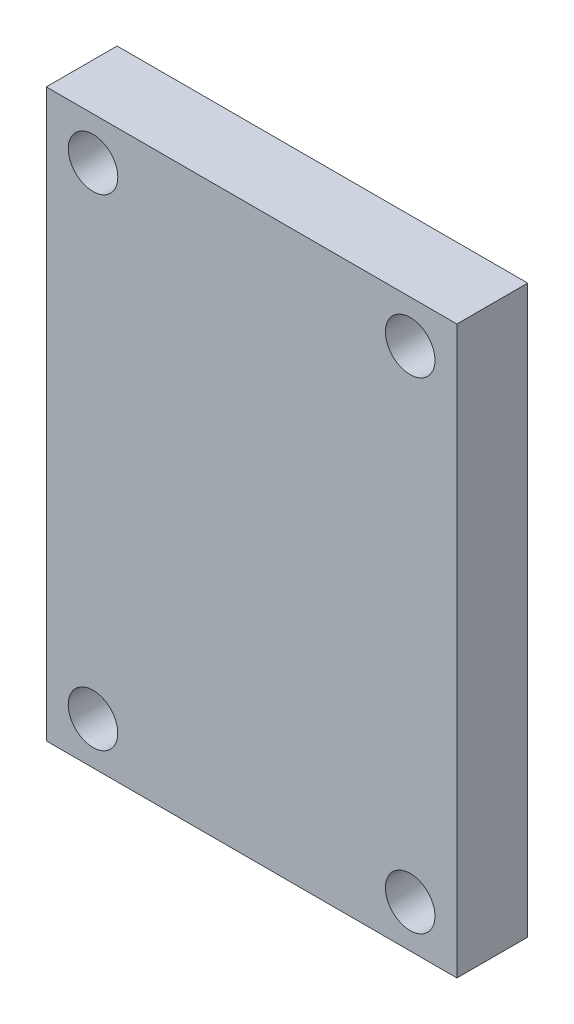
SolidWorks part; units mm, degrees
ref_plane "정면" through (0, 0, 0) normal (0, 0, 1) x (1, 0, 0)
ref_plane "윗면" through (0, 0, 0) normal (0, 1, 0) x (1, 0, 0)
ref_plane "우측면" through (0, 0, 0) normal (1, 0, 0) x (0, 0, -1)
sketch "스케치1" plane through (0, 0, 0) normal (0, 0, 1) x (1, 0, 0)
  line L2 (14.5, -20) -> (-14.5, -20)
  line L3 (14.5, -20) -> (14.5, 20)
  line L4 (14.5, 20) -> (-14.5, 20)
  line L5 (-14.5, -20) -> (-14.5, 20)
  line L6 (14.5, -20) -> (-14.5, 20) construction
  line L7 (14.5, 20) -> (-14.5, -20) construction
  line L9 (-14.5, 17) -> (14.5, 17) construction
  line L10 (-14.5, 0) -> (14.5, 0) construction
  circle A0 centre (11.1994, 17) radius 1.75
  circle A1 centre (-11.1994, 17) radius 1.75
  circle A2 centre (11.1994, -17) radius 1.75
  circle A6 centre (-11.1994, -17) radius 1.75
  point P3 (0, 0)
  dimension "D3" = 40
  dimension "D1" = 3
extrude "보스-돌출1" add sketch "스케치1" along normal blind 5
ref_plane "평면1" through (0, 0, 2) normal (0, 0, 1) x (1, 0, 0)
ref_plane "평면2" through (0, 0, 4.5) normal (0, 0, -1) x (-1, 0, 0)
sketch "스케치3" plane through (0, 0, 4.5) normal (0, 0, -1) x (-1, 0, 0)
  line L0 (14.5, 20) -> (14.5, -20) construction
  line L1 (-14.5, 20) -> (14.5, 20)
  line L2 (-14.5, 20) -> (-14.5, 8)
  line L3 (-14.5, 8) -> (14.5, 8)
  line L4 (14.5, 20) -> (14.5, 8)
